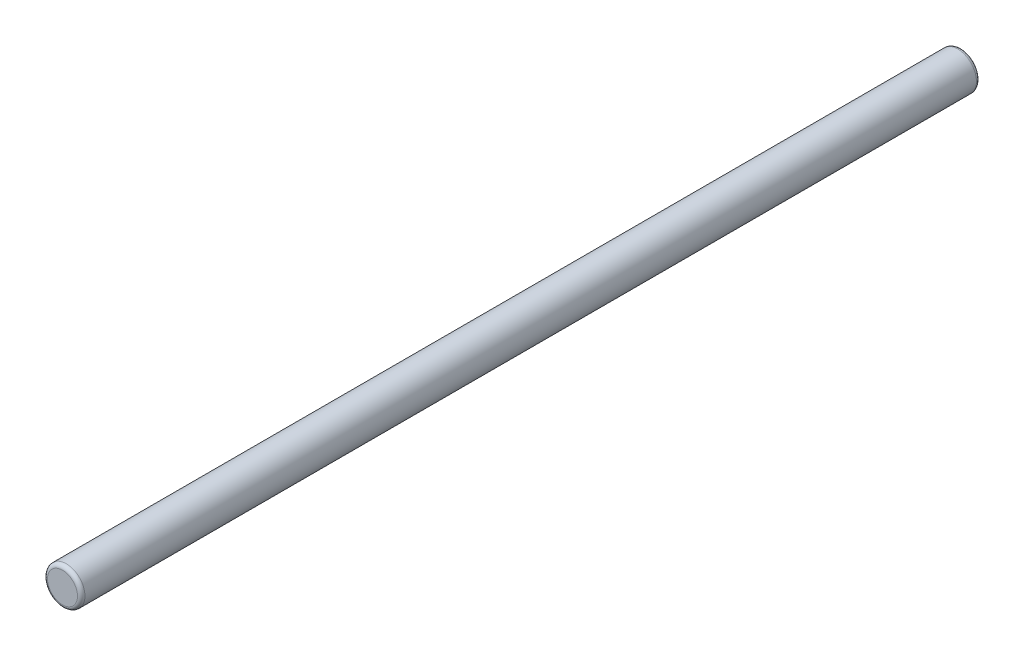
SolidWorks part; units mm, degrees
ref_plane "Front Plane" through (0, 0, 0) normal (0, 0, 1) x (1, 0, 0)
ref_plane "Top Plane" through (0, 0, 0) normal (0, 1, 0) x (1, 0, 0)
ref_plane "Right Plane" through (0, 0, 0) normal (1, 0, 0) x (0, 0, -1)
sketch "Sketch1" plane through (0, 0, 0) normal (0, 0, 1) x (1, 0, 0)
  circle A0 centre (0, 0) radius 2.5
  dimension "D1" = 5
extrude "Boss-Extrude1" add sketch "Sketch1" along normal blind 120
fillet "Fillet1" radius 0.5 2 edges at (2.5, 0, 120) (2.5, 0, 0)
